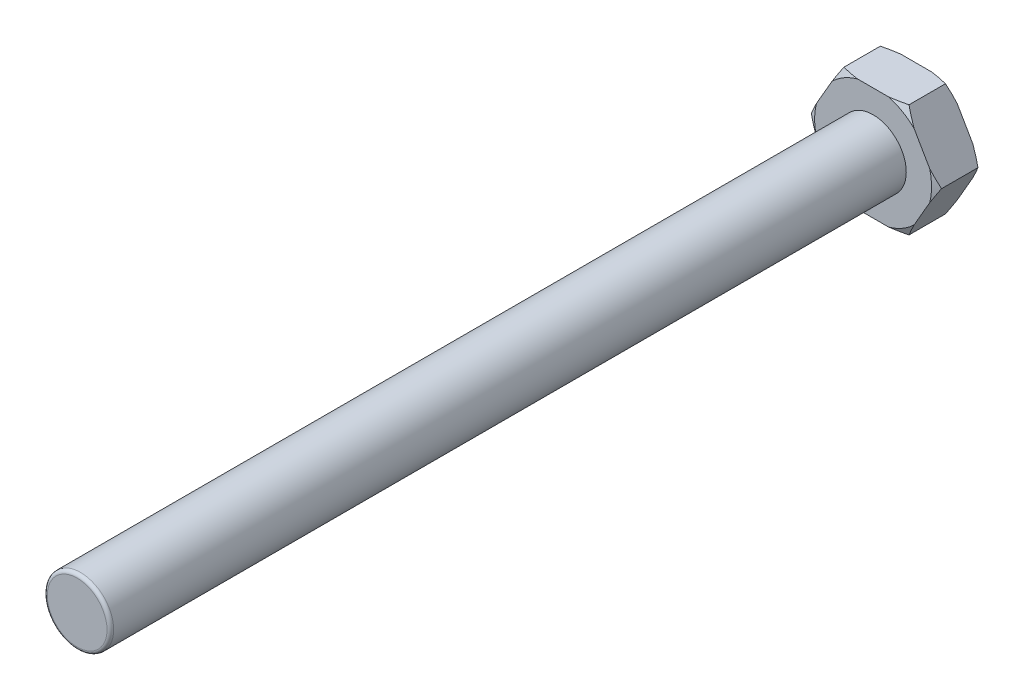
SolidWorks part; units mm, degrees
material "1.0036 (S235JRG1)"
ref_plane "Ön Düzlem" through (0, 0, 0) normal (0, 0, 1) x (1, 0, 0)
ref_plane "Üst Düzlem" through (0, 0, 0) normal (0, 1, 0) x (1, 0, 0)
ref_plane "Sağ Düzlem" through (0, 0, 0) normal (1, 0, 0) x (0, 0, -1)
sketch "Çizim1" plane through (0, 0, 0) normal (0, 0, 1) x (1, 0, 0)
  line L1 (9.815, 0) -> (4.9075, 8.5)
  line L2 (4.9075, 8.5) -> (-4.9075, 8.5)
  line L3 (-4.9075, 8.5) -> (-9.815, 0)
  line L4 (-9.815, 0) -> (-4.9075, -8.5)
  line L5 (-4.9075, -8.5) -> (4.9075, -8.5)
  line L6 (4.9075, -8.5) -> (9.815, 0)
  circle A0 centre (0, 0) radius 8.5 construction
  dimension "D1" = 17
extrude "Yükseklik-Ekstrüzyon1" add sketch "Çizim1" along normal blind 6.5
sketch "Çizim2" plane through (0, 0, 6.5) normal (0, 0, 1) x (1, 0, 0)
  circle A0 centre (0, 0) radius 5
  dimension "D1" = 10
extrude "Yükseklik-Ekstrüzyon2" add sketch "Çizim2" along normal blind 120
cosmetic thread "Kozmetik Diş Açma1" parameters "D2"=8.344
sketch "Çizim3" plane through (0, 0, 0) normal (0, 1, 0) x (1, 0, 0)
  line L0 (-9.815, 0) -> (-8.815, 0)
  line L1 (-4.9075, 0) -> (-9.815, 0) construction
  line L2 (-8.815, 0) -> (-9.815, -0.5)
  line L3 (-9.815, -6.5) -> (-9.815, 0) construction
  line L4 (-9.815, -0.5) -> (-9.815, 0)
  line L9 (-9.815, -6.5) -> (-9.815, -6)
  line L10 (-9.815, -6) -> (-8.815, -6.5)
  line L11 (-4.9075, -6.5) -> (-9.815, -6.5) construction
  line L12 (-8.815, -6.5) -> (-9.815, -6.5)
  line L13 (0, 0) -> (0, -6.5) construction
  line L14 (-5, -6.5) -> (5, -6.5) construction
  dimension "D1" = 1
  dimension "D2" = 0.5
  dimension "D3" = 0.5
  dimension "D4" = 1
revolve "Kes-Döndür1" cut sketch "Çizim3" angle 360 about L13
fillet "Radyus1" radius 0.5 1 edges at (5, 0, 126.5)
